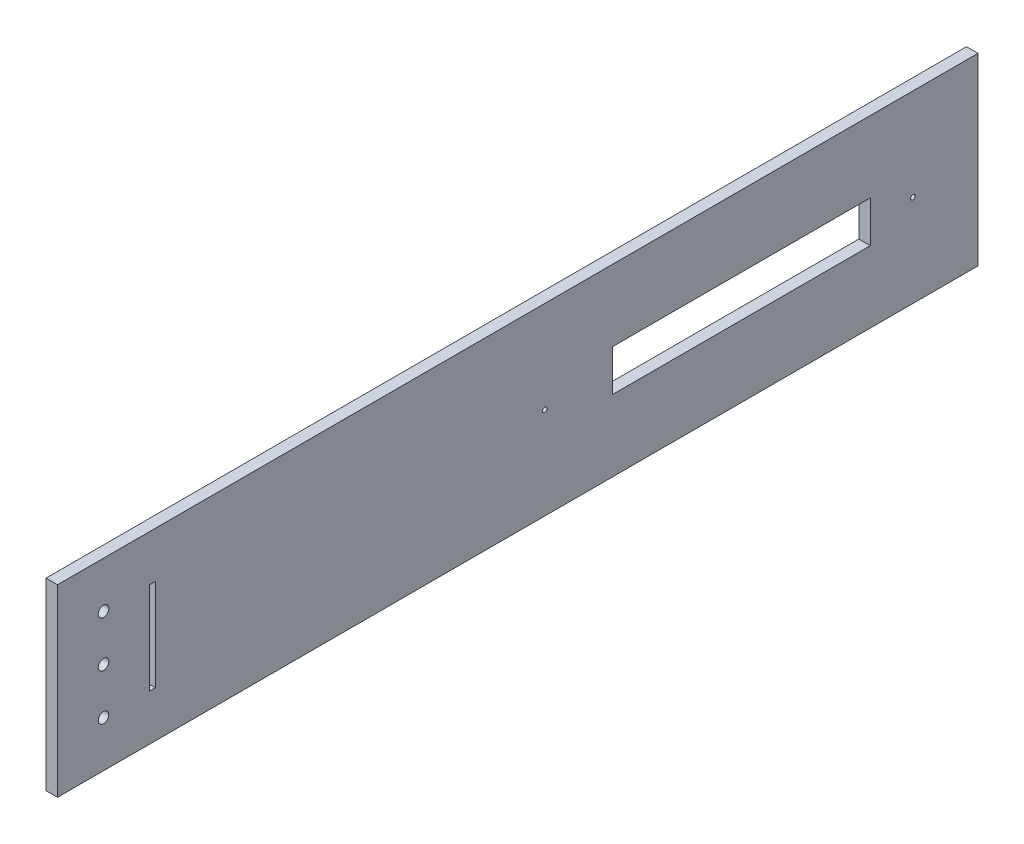
SolidWorks part; units mm, degrees
ref_plane "Front Plane" through (0, 0, 0) normal (0, 0, 1) x (1, 0, 0)
ref_plane "Top Plane" through (0, 0, 0) normal (0, 1, 0) x (1, 0, 0)
ref_plane "Right Plane" through (0, 0, 0) normal (1, 0, 0) x (0, 0, -1)
sketch "Sketch1" plane through (0, 0, 0) normal (1, 0, 0) x (0, 0, -1)
  line L0 (0, 0) -> (-254, 0) construction
  line L1 (0, 25.4) -> (-254, 25.4)
  line L2 (0, 25.4) -> (0, -25.4)
  line L3 (0, -25.4) -> (-254, -25.4)
  line L4 (-254, 25.4) -> (-254, -25.4)
  line L5 (-100.838, 5.715) -> (-29.718, 5.715) construction
  line L6 (-29.718, 5.715) -> (-100.8721, 5.715)
  line L7 (-29.718, 5.715) -> (-29.718, -5.715)
  line L8 (-29.718, -5.715) -> (-100.8721, -5.715)
  line L9 (-100.8721, 5.715) -> (-100.8721, -5.715)
  line L10 (-32.3851, -5.715) -> (-100.8721, -5.715) construction
  line L11 (-227.0125, 0) -> (-228.6, 0) construction
  line L12 (-227.0125, 12.7) -> (-228.6, 12.7)
  line L13 (-227.0125, 12.7) -> (-227.0125, -12.7)
  line L14 (-227.0125, -12.7) -> (-228.6, -12.7)
  line L15 (-228.6, 12.7) -> (-228.6, -12.7)
  line L16 (-241.3, 12.7) -> (-241.3, -12.7) construction
  line L17 (-215.9, -139.7) -> (-215.9, 139.7) construction
  line L18 (-29.718, 5.715) -> (-29.718, -5.715) construction
  line L19 (-100.8721, -5.715) -> (-100.8721, 5.715) construction
  circle A0 centre (-17.9578, 0) radius 0.635
  circle A1 centre (-119.5578, 0) radius 0.635
  circle A2 centre (-119.5578, 0) radius 0.635 construction
  circle A3 centre (-17.9578, 0) radius 0.635 construction
  circle A4 centre (-241.3, 0) radius 1.4605
  circle A5 centre (-241.3, 12.7) radius 1.4605
  circle A8 centre (-241.3, -12.7) radius 1.4605
  dimension "D6" = 2.921
  dimension "D7" = 2.921
  dimension "D10" = 2.921
  dimension "D1" = 50.8
  dimension "D2" = 25.4
  dimension "D3" = 1.5875
  dimension "D4" = 25.4
  dimension "D5" = 12.7
  dimension "D8" = 38.1
extrude "Boss-Extrude1" add sketch "Sketch1" against normal blind 3.175
equation "\"D6@Sketch1\"=\"D7@Sketch1\""
equation "\"D10@Sketch1\"=\"D7@Sketch1\""
